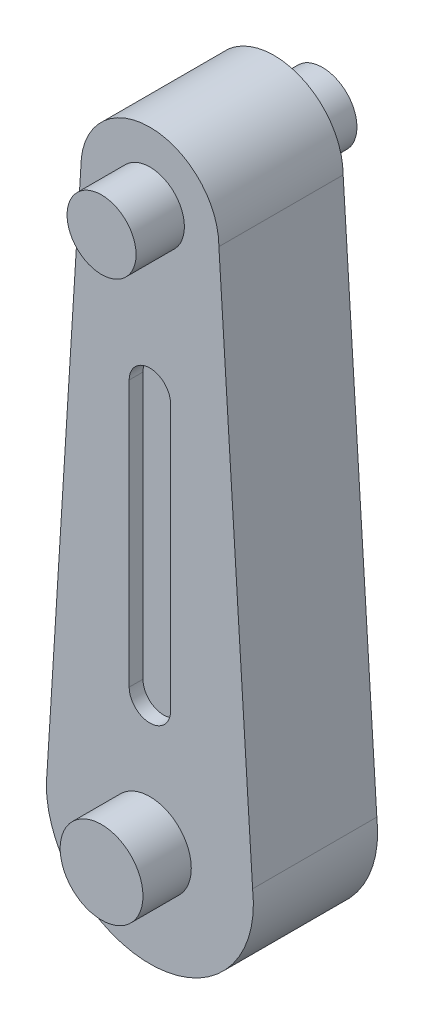
SolidWorks part; units mm, degrees
material "AISI 1020"
ref_plane "Front Plane" through (0, 0, 0) normal (0, 0, 1) x (1, 0, 0)
ref_plane "Top Plane" through (0, 0, 0) normal (0, 1, 0) x (1, 0, 0)
ref_plane "Right Plane" through (0, 0, 0) normal (1, 0, 0) x (0, 0, -1)
sketch "Sketch1" plane through (0, 0, 0) normal (0, 0, 1) x (1, 0, 0)
  line L0 (-50, 212.5) -> (-74.4163, -178.1615)
  line L1 (75, -262.5) -> (-75, -262.5) construction
  line L2 (75, -262.5) -> (75, 262.5) construction
  line L3 (75, 262.5) -> (-75, 262.5) construction
  line L4 (-75, -262.5) -> (-75, 262.5) construction
  line L5 (75, -262.5) -> (-75, 262.5) construction
  line L6 (75, 262.5) -> (-75, -262.5) construction
  line L7 (50, 212.5) -> (74.4163, -178.1615)
  arc A0 (-74.4163, -178.1615) -> (74.4163, -178.1615) centre (0, -187.5) ccw
  arc A1 (50, 212.5) -> (-50, 212.5) centre (0, 212.5) ccw
  point P0 (0, 0)
  dimension "D3" = 150
  dimension "D4" = 100
  dimension "D1" = 525
  dimension "D2" = 150
  dimension "D5" = 390.6615
  dimension "D6" = 390.6615
extrude "Boss-Extrude1" add sketch "Sketch1" along normal mid plane 90
sketch "Sketch2" plane through (0, 0, 45) normal (0, 0, 1) x (1, 0, 0)
  circle A0 centre (0, 212.5) radius 25
  arc A1 (50, 212.5) -> (-50, 212.5) centre (0, 212.5) ccw construction
  circle A2 centre (0, -187.5) radius 30
  arc A3 (-74.4163, -178.1615) -> (74.4163, -178.1615) centre (0, -187.5) ccw construction
  point P7 (0, 262.5)
  point P12 (0, -262.5)
  point P13 (0, 0)
  dimension "D1" = 50
  dimension "D3" = 60
  dimension "D2" = 50
  dimension "D4" = 75
extrude "Boss-Extrude2" add sketch "Sketch2" along normal blind 35
mirror "Mirror1" about plane through (0, 0, 0) normal (0, 0, 1) of "Boss-Extrude2"
sketch "Sketch3" plane through (0, 0, 45) normal (0, 0, 1) x (1, 0, 0)
  line L0 (0, 96.3528) -> (0, -96.3528) construction
  line L1 (15, 96.3528) -> (15, -96.3528)
  line L2 (-15, 96.3528) -> (-15, -96.3528)
  arc A0 (15, 96.3528) -> (-15, 96.3528) centre (0, 96.3528) ccw
  arc A1 (-15, -96.3528) -> (15, -96.3528) centre (0, -96.3528) ccw
  point P3 (0, 0)
  point P8 (0, 0)
  point P9 (0, 0)
  dimension "D1" = 15
  dimension "D2" = 192.7057
extrude "Cut-Extrude1" cut sketch "Sketch3" against normal blind 10
mirror "Mirror2" about plane through (0, 0, 0) normal (0, 0, 1) of "Cut-Extrude1"
